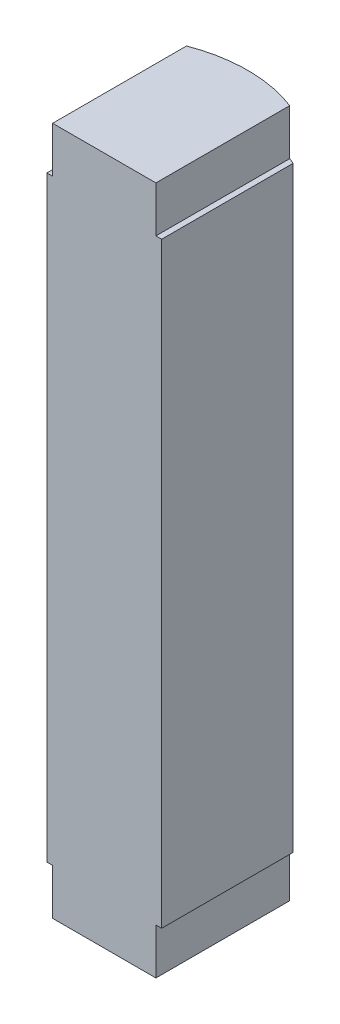
SolidWorks part; units mm, degrees
ref_plane "Front Plane" through (0, 0, 0) normal (0, 0, 1) x (1, 0, 0)
ref_plane "Top Plane" through (0, 0, 0) normal (0, 1, 0) x (1, 0, 0)
ref_plane "Right Plane" through (0, 0, 0) normal (1, 0, 0) x (0, 0, -1)
sketch "Sketch2" plane through (0, 0, 0) normal (0, 1, 0) x (1, 0, 0)
  line L0 (-5, 0) -> (5, 0)
  line L1 (5, 0) -> (5, 11.4564)
  line L3 (-5, 11.4564) -> (-5, 0)
  arc A0 (5, 11.4564) -> (-5, 11.4564) centre (0, 0) ccw
  dimension "D1" = 12.5
  dimension "D2" = 10
extrude "Boss-Extrude1" add sketch "Sketch2" along normal blind 60
sketch "Sketch3" plane through (0, 0, 0) normal (0, 0, 1) x (1, 0, 0)
  line L0 (0, 0) -> (0, 3.9559) construction
  line L1 (-5, 0) -> (-4.5, 0)
  line L2 (-5, 0) -> (-5, 4)
  line L3 (-5, 4) -> (-4.5, 4)
  line L4 (-4.5, 0) -> (-4.5, 4)
  line L5 (4.5, 0) -> (4.5, 4)
  line L6 (5, 4) -> (4.5, 4)
  line L7 (5, 0) -> (5, 4)
  line L8 (5, 0) -> (4.5, 0)
  line L9 (-5, 30) -> (5, 30) construction
  line L10 (-5, 60) -> (-5, 0) construction
  line L11 (5, 60) -> (5, 0) construction
  line L12 (5, 60) -> (4.5, 60)
  line L13 (5, 60) -> (5, 56)
  line L14 (5, 56) -> (4.5, 56)
  line L15 (4.5, 60) -> (4.5, 56)
  line L16 (-4.5, 60) -> (-4.5, 56)
  line L17 (-5, 56) -> (-4.5, 56)
  line L18 (-5, 60) -> (-5, 56)
  line L19 (-5, 60) -> (-4.5, 60)
  dimension "D1" = 4
  dimension "D2" = 0.5
extrude "Cut-Extrude1" cut sketch "Sketch3" against normal blind 20
